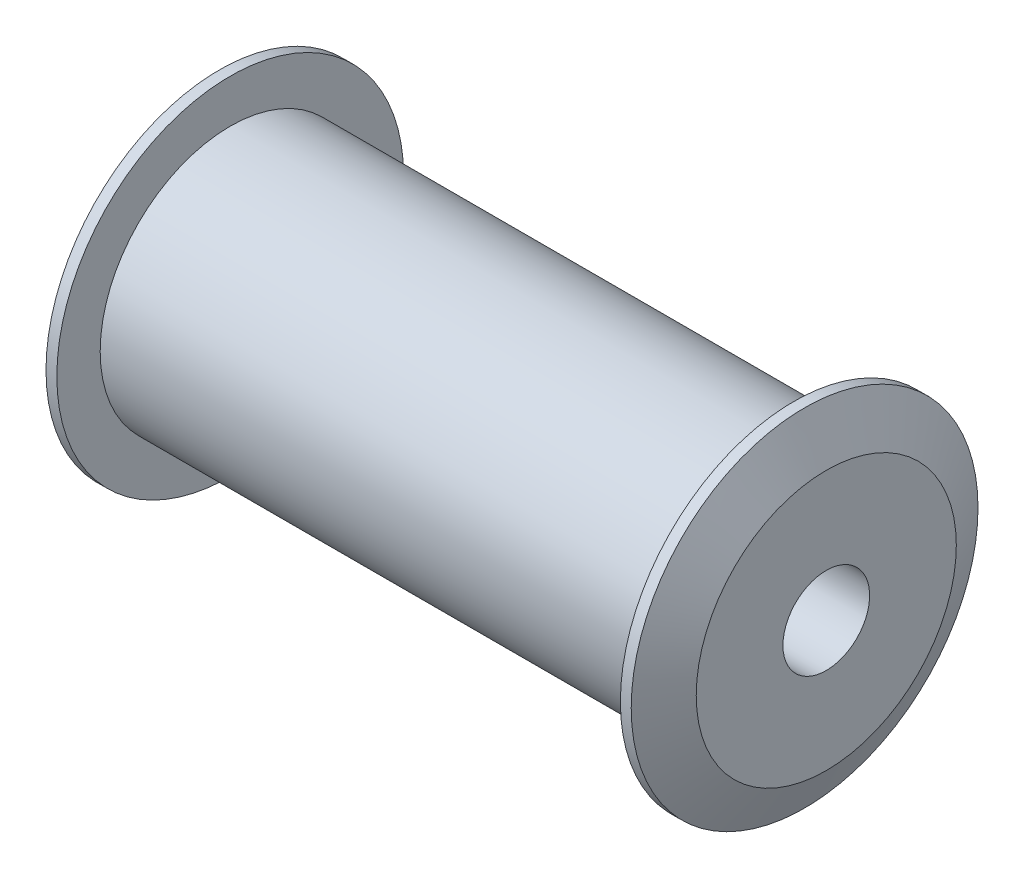
SolidWorks part; units mm, degrees
material "ABS"
ref_plane "前视基准面" through (0, 0, 0) normal (0, 0, 1) x (1, 0, 0)
ref_plane "上视基准面" through (0, 0, 0) normal (0, 1, 0) x (1, 0, 0)
ref_plane "右视基准面" through (0, 0, 0) normal (1, 0, 0) x (0, 0, -1)
sketch "草图2" plane through (0, 0, 0) normal (0, 0, 1) x (1, 0, 0)
  line L0 (-54.7332, 47) -> (96.9258, 47) construction
  line L1 (0, 65.1685) -> (0, 23.0963) construction
  line L2 (-13, 53) -> (13, 53)
  line L3 (-14.5, 55) -> (-14.5, 49)
  line L4 (0, -47.5855) -> (0, 47.5855) construction
  line L5 (14.5, 55) -> (14.5, 49)
  line L6 (-14.5, 55) -> (-13, 55)
  line L7 (-13, 55) -> (-13, 53)
  line L8 (0, -39.5263) -> (0, 39.5263) construction
  line L9 (14.5, 55) -> (13, 55)
  line L10 (13, 55) -> (13, 53)
  line L12 (0, 28.8756) -> (0, 1.3387) construction
  line L13 (-14.5, 49) -> (14.5, 49)
  dimension "D1" = 47
  dimension "D2" = 8
  dimension "D3" = 6
  dimension "D4" = 1.5
  dimension "D5" = 1.5
  dimension "D6" = 2
  dimension "D7" = 29
revolve "旋转1" add sketch "草图2" angle 360 about L0
chamfer "倒角1" distance 1 distance2 2 1 edges at (-14.5, 47, 8)
chamfer "倒角2" distance 2 distance2 1 1 edges at (14.5, 47, 8)
